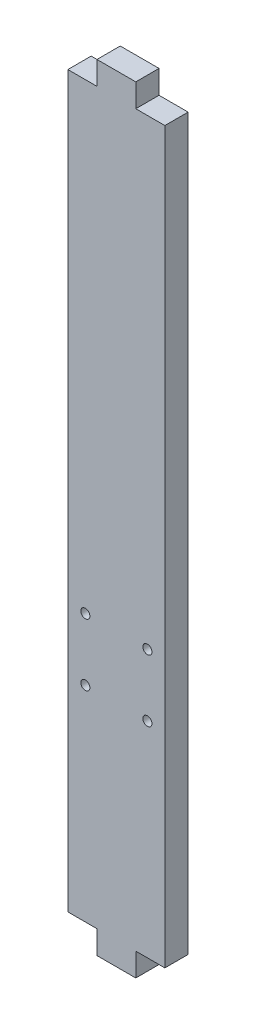
SolidWorks part; units mm, degrees
ref_plane "Plan de face" through (0, 0, 0) normal (0, 0, 1) x (1, 0, 0)
ref_plane "Plan de dessus" through (0, 0, 0) normal (0, 1, 0) x (1, 0, 0)
ref_plane "Plan de droite" through (0, 0, 0) normal (1, 0, 0) x (0, 0, -1)
sketch "Esquisse1" plane through (0, 0, 0) normal (0, 0, 1) x (1, 0, 0)
  line L1 (-12.5, 100) -> (12.5, 100)
  line L2 (-12.5, 100) -> (-12.5, -100)
  line L3 (-12.5, -100) -> (12.5, -100)
  line L4 (12.5, 100) -> (12.5, -100)
  point P7 (10.3234, 0.778)
  dimension "D1" = 200
  dimension "D2" = 25
  dimension "D3" = 100
  dimension "D4" = 12.5
extrude "Boss.-Extru.1" add sketch "Esquisse1" along normal blind 6
sketch "Esquisse2" plane through (0, 0, 6) normal (0, 0, 1) x (1, 0, 0)
  line L0 (-12.5, -100) -> (12.5, -100) construction
  line L1 (-12.5, 100) -> (-12.5, -100) construction
  circle A0 centre (8, -41.15) radius 1.175
  circle A1 centre (-8, -41.15) radius 1.175
  circle A2 centre (-8, -25.15) radius 1.175
  circle A3 centre (8, -25.15) radius 1.175
  dimension "D1" = 2.35
  dimension "D2" = 2.35
  dimension "D3" = 2.35
  dimension "D4" = 2.35
  dimension "D5" = 16
  dimension "D6" = 16
  dimension "D7" = 16
  dimension "D8" = 16
  dimension "D10" = 58.85
  dimension "D11" = 4.5
  dimension "D12" = 4.5
extrude "Enlèv. mat.-Extru.1" cut sketch "Esquisse2" against normal blind 6
sketch "Esquisse3" plane through (0, 0, 6) normal (0, 0, 1) x (1, 0, 0)
  line L0 (43.2899, 0) -> (-75.8823, 0) construction
  line L1 (-12.5, -100) -> (-5, -100)
  line L2 (-12.5, -100) -> (-12.5, -94)
  line L3 (-12.5, -94) -> (-5, -94)
  line L4 (-5, -100) -> (-5, -94)
  line L5 (12.5, -100) -> (5, -100)
  line L6 (12.5, -100) -> (12.5, -94)
  line L7 (12.5, -94) -> (5, -94)
  line L8 (5, -100) -> (5, -94)
  line L9 (5, 100) -> (5, 94)
  line L10 (12.5, 94) -> (5, 94)
  line L11 (12.5, 100) -> (12.5, 94)
  line L12 (12.5, 100) -> (5, 100)
  line L13 (-5, 100) -> (-5, 94)
  line L14 (-12.5, 94) -> (-5, 94)
  line L15 (-12.5, 100) -> (-12.5, 94)
  line L16 (-12.5, 100) -> (-5, 100)
  dimension "D1" = 10
  dimension "D2" = 7.5
  dimension "D3" = 6
  dimension "D4" = 6
extrude "Enlèv. mat.-Extru.2" cut sketch "Esquisse3" against normal blind 6
